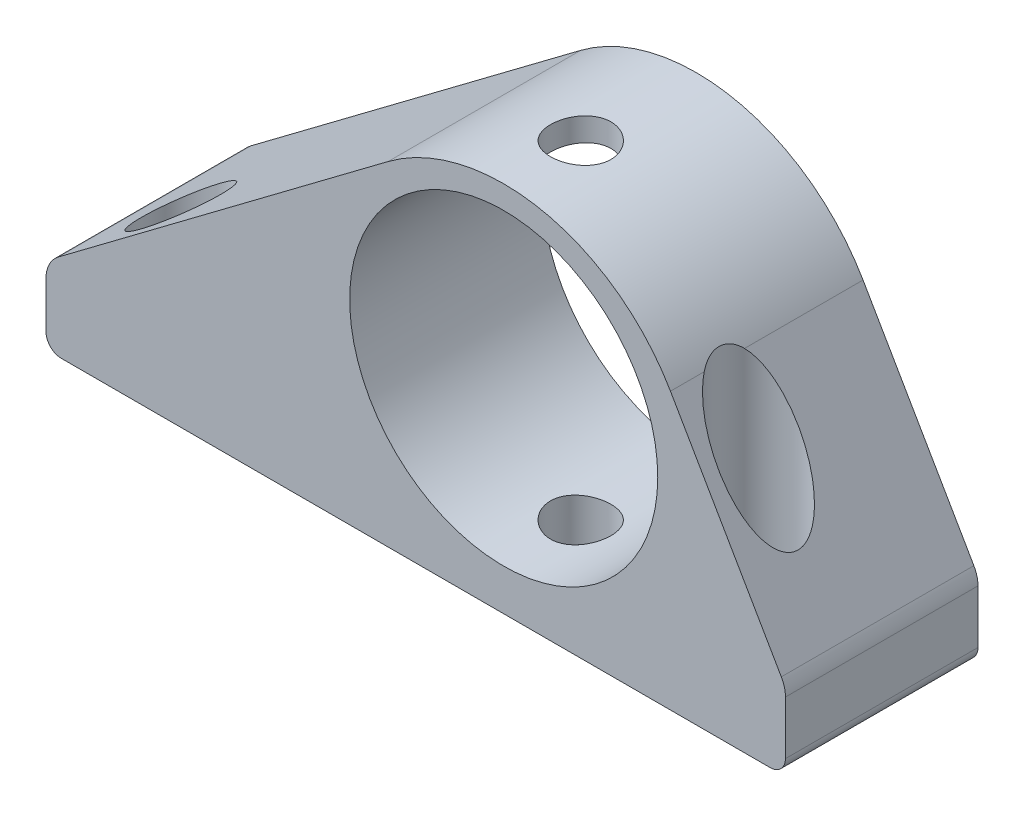
SolidWorks part; units mm, degrees
ref_plane "Alzado" through (0, 0, 0) normal (0, 0, 1) x (1, 0, 0)
ref_plane "Planta" through (0, 0, 0) normal (0, 1, 0) x (1, 0, 0)
ref_plane "Vista lateral" through (0, 0, 0) normal (1, 0, 0) x (0, 0, -1)
sketch "Croquis1" plane through (0, 0, 0) normal (0, 0, 1) x (1, 0, 0)
  line L4 (30.48, 0) -> (-30.48, 0)
  line L5 (-30.48, 0) -> (-30.48, 6.35)
  line L6 (-30.48, 6.35) -> (12.0465, 38.2778)
  line L7 (12.0465, 38.2778) -> (30.48, 6.35)
  line L8 (30.48, 6.35) -> (30.48, 0)
  line L9 (0, 0) -> (0, 44.0233) construction
  point P11 (0, 0)
  dimension "D1" = 6.35
  dimension "D2" = 38.2778
  dimension "D3" = 60.96
  dimension "D4" = 30
extrude "Saliente-Extruir1" add sketch "Croquis1" along normal blind 15.875
fillet "Redondeo1" radius 15.875 1 edges at (12.0465, 38.2778, 7.9375)
sketch "Croquis2" plane through (0, 0, 15.875) normal (0, 0, 1) x (1, 0, 0)
  line L0 (30.48, 6.35) -> (21.0022, 22.7661) construction
  circle A0 centre (7.254, 16.0986) radius 9.525
  arc A1 (21.0022, 22.7661) -> (-2.2773, 27.5239) centre (7.254, 14.8286) ccw construction
  dimension "D1" = 5.08
  dimension "D2" = 19.05
  dimension "D3" = 15.24
extrude "Cortar-Extruir1" cut sketch "Croquis2" against normal up to next
sketch "Croquis3" plane through (0, 0, 15.875) normal (0, 0, 1) x (1, 0, 0)
  circle A0 centre (7.254, 16.0986) radius 12.7
  dimension "D1" = 25.4
extrude "Cortar-Extruir2" cut sketch "Croquis3" against normal through all
sketch "Croquis4" plane through (0, 0, 0) normal (0, -1, 0) x (1, 0, 0)
  line L0 (-30.48, 15.875) -> (-30.48, 0) construction
  line L1 (-30.48, 15.875) -> (30.48, 15.875) construction
  line L2 (0, 0) -> (0, 12.065) construction
  line L3 (-30.48, 0) -> (30.48, 0) construction
  line L5 (19.954, 15.875) -> (-5.446, 15.875) construction
  line L6 (19.954, 15.875) -> (-5.446, 15.875)
  circle A0 centre (-23.8125, 11.43) radius 3.2639
  circle A1 centre (23.8125, 11.43) radius 3.2639
  circle A3 centre (7.254, 9.525) radius 2.4892
  point P21 (7.254, 15.875)
  dimension "D1" = 6.5278
  dimension "D4" = 4.9784
  dimension "D5" = 6.35
  dimension "D2" = 6.6675
  dimension "D3" = 4.445
extrude "Cortar-Extruir3" cut sketch "Croquis4" against normal through all contours A3 | A0 | A1
fillet "Redondeo2" radius 2.54 2 edges at (-30.48, 6.35, 7.9375) (30.48, 6.35, 7.9375)
fillet "Redondeo3" radius 1.27 2 edges at (30.48, 0, 7.9375) (-30.48, 0, 7.9375)
